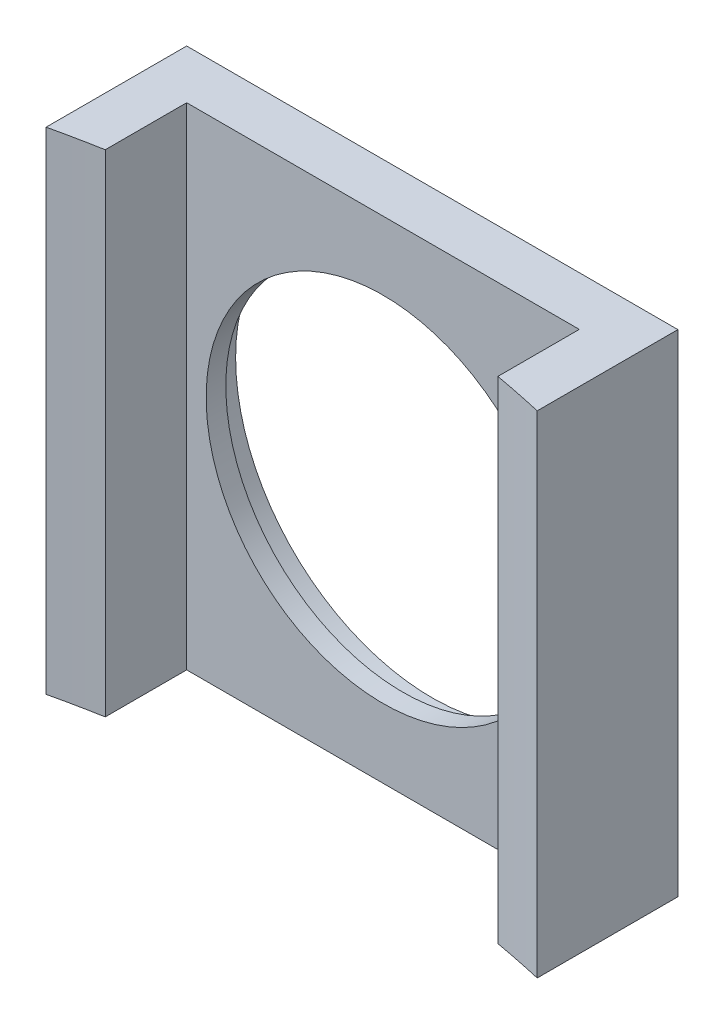
SolidWorks part; units mm, degrees
ref_plane "Front Plane" through (0, 0, 0) normal (0, 0, 1) x (1, 0, 0)
ref_plane "Top Plane" through (0, 0, 0) normal (0, 1, 0) x (1, 0, 0)
ref_plane "Right Plane" through (0, 0, 0) normal (1, 0, 0) x (0, 0, -1)
sketch "Sketch2" plane through (0, 0, 0) normal (0, 0, 1) x (1, 0, 0)
  line L1 (-37.3016, 29.4974) -> (12.6984, 29.4974)
  line L2 (-37.3016, 29.4974) -> (-37.3016, -20.5026)
  line L3 (-37.3016, -20.5026) -> (12.6984, -20.5026)
  line L4 (12.6984, 29.4974) -> (12.6984, -20.5026)
  line L5 (-37.3016, 29.4974) -> (12.6984, -20.5026) construction
  line L6 (-37.3016, -20.5026) -> (12.6984, 29.4974) construction
  point P0 (-12.3016, 4.4974)
  dimension "D1" = 50
  dimension "D2" = 50
extrude "Boss-Extrude1" add sketch "Sketch2" along normal blind 5
sketch "Sketch3" plane through (0, 0, 5) normal (0, 0, 1) x (1, 0, 0)
  line L0 (-37.3016, -20.5026) -> (12.6984, -20.5026) construction
  line L1 (-37.3016, 29.4974) -> (-32.3016, 29.4974)
  line L2 (-37.3016, 29.4974) -> (-37.3016, -20.5026)
  line L3 (-37.3016, -20.5026) -> (-32.3016, -20.5026)
  line L4 (-32.3016, 29.4974) -> (-32.3016, -20.5026)
  line L6 (12.6984, 29.4974) -> (7.6624, 29.4974)
  line L7 (12.6984, 29.4974) -> (12.6984, -20.5026)
  line L8 (12.6984, -20.5026) -> (7.6624, -20.5026)
  line L9 (7.6624, 29.4974) -> (7.6624, -20.5026)
  dimension "D1" = 5
  dimension "D2" = 5.036
extrude "Boss-Extrude2" add sketch "Sketch3" along normal blind 11
sketch "Sketch5" plane through (0, 0, 0) normal (0, 0, 1) x (1, 0, 0)
  circle A0 centre (-12.3196, 4.5295) radius 18
  dimension "D1" = 36
extrude "Cut-Extrude3" cut sketch "Sketch5" along direction (0, 0, 1) on the side against the normal through all and the other way through all
sketch "Sketch6" plane through (0, 0, 0) normal (0, 0, -1) x (-1, 0, 0)
  circle A0 centre (12.3196, 4.5295) radius 20
  dimension "D1" = 40
extrude "Cut-Extrude4" cut sketch "Sketch6" against normal blind 3 contours A0
sketch "Sketch7" plane through (0, 0, 0) normal (0, 1, 0) x (1, 0, 0)
  line L0 (12.6984, 0) -> (-37.3016, 0) construction
  circle A0 centre (-12.3196, -124) radius 112.5
  dimension "D1" = 225
  dimension "D2" = 124
extrude "Cut-Extrude5" cut sketch "Sketch7" against normal through all both and the other way through all
